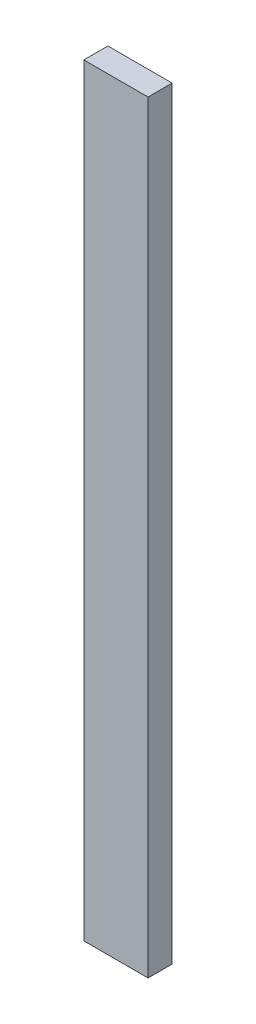
SolidWorks part; units mm, degrees
material "AISI 1020"
ref_plane "Front Plane" through (0, 0, 0) normal (0, 0, 1) x (1, 0, 0)
ref_plane "Top Plane" through (0, 0, 0) normal (0, 1, 0) x (1, 0, 0)
ref_plane "Right Plane" through (0, 0, 0) normal (1, 0, 0) x (0, 0, -1)
sketch "Sketch2" plane through (0, 0, 0) normal (0, 0, 1) x (1, 0, 0)
  line L1 (-25.4, -301.625) -> (25.4, -301.625)
  line L2 (-25.4, -301.625) -> (-25.4, 301.625)
  line L3 (-25.4, 301.625) -> (25.4, 301.625)
  line L4 (25.4, -301.625) -> (25.4, 301.625)
  line L5 (-25.4, -301.625) -> (25.4, 301.625) construction
  line L6 (-25.4, 301.625) -> (25.4, -301.625) construction
  point P0 (0, 0)
  dimension "D1" = 603.25
  dimension "D2" = 50.8
extrude "Boss-Extrude1" add sketch "Sketch2" along normal blind 19.05
equation "\"A\"= 100"
equation "\"B\"= 100"
equation "\"C\"= 100"
equation "\"D\"= 100"
equation "\"E\"= 100"
